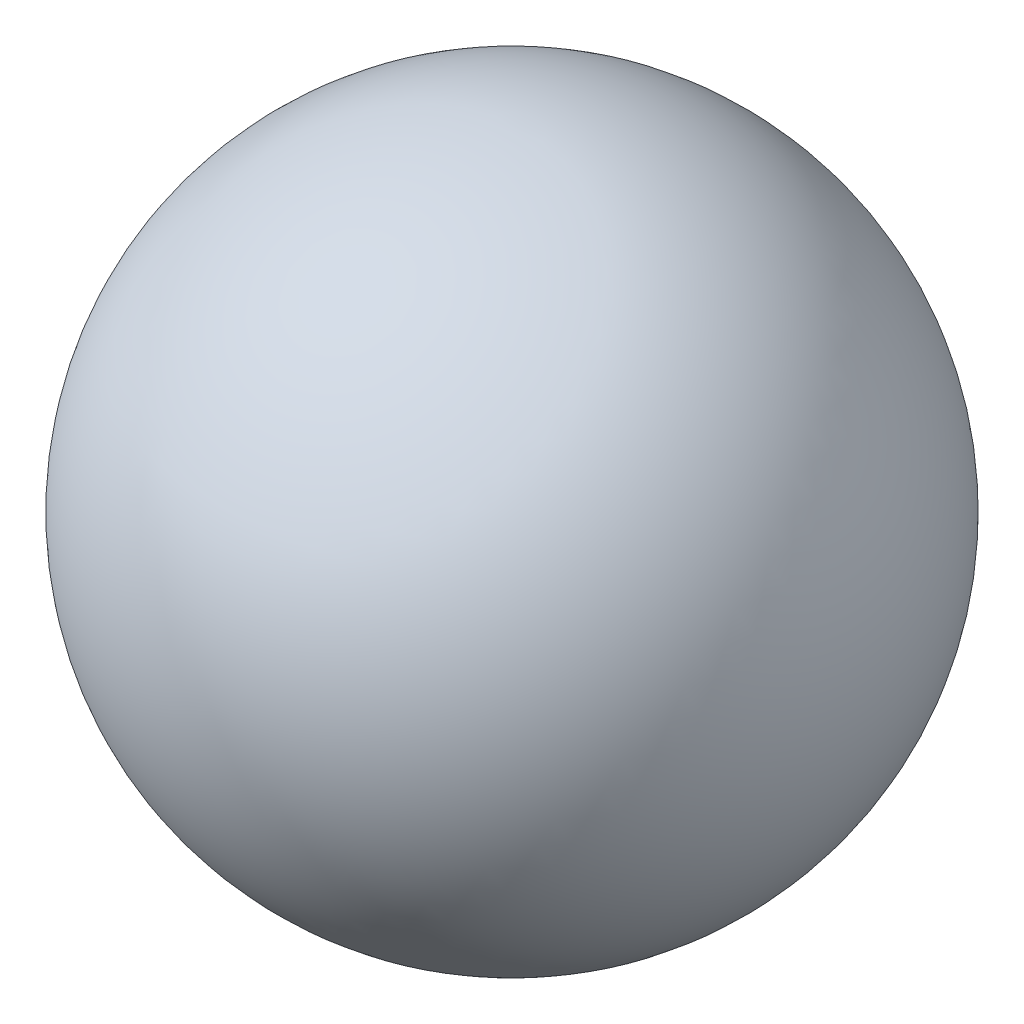
SolidWorks part; units mm, degrees
material "Polyurethane Foam Rigid"
ref_plane "Front Plane" through (0, 0, 0) normal (0, 0, 1) x (1, 0, 0)
ref_plane "Top Plane" through (0, 0, 0) normal (0, 1, 0) x (1, 0, 0)
ref_plane "Right Plane" through (0, 0, 0) normal (1, 0, 0) x (0, 0, -1)
sketch "Sketch1" plane through (0, 0, 0) normal (0, 0, 1) x (1, 0, 0)
  line L0 (0, -35) -> (0, 35)
  arc A0 (0, 35) -> (0, -35) centre (0, 0) ccw
  point P4 (0, 0)
  dimension "D1" = 70
revolve "Revolve1" add sketch "Sketch1" angle 360 about L0
